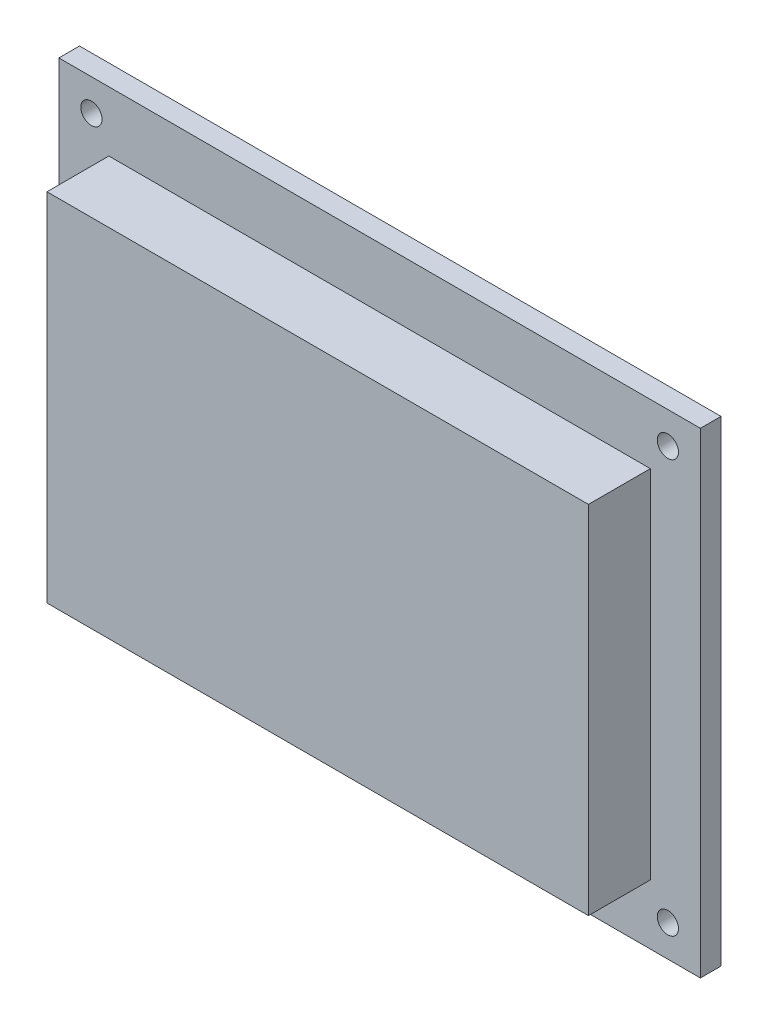
SolidWorks part; units mm, degrees
ref_plane "Front Plane" through (0, 0, 0) normal (0, 0, 1) x (1, 0, 0)
ref_plane "Top Plane" through (0, 0, 0) normal (0, 1, 0) x (1, 0, 0)
ref_plane "Right Plane" through (0, 0, 0) normal (1, 0, 0) x (0, 0, -1)
sketch "Sketch1" plane through (0, 0, 0) normal (0, 0, 1) x (1, 0, 0)
  line L1 (-49.3395, -36.6141) -> (49.3395, -36.6141)
  line L2 (-49.3395, -36.6141) -> (-49.3395, 36.6141)
  line L3 (-49.3395, 36.6141) -> (49.3395, 36.6141)
  line L4 (49.3395, -36.6141) -> (49.3395, 36.6141)
  line L5 (-49.3395, -36.6141) -> (49.3395, 36.6141) construction
  line L6 (-49.3395, 36.6141) -> (49.3395, -36.6141) construction
  point P0 (0, 0)
  dimension "D1" = 73.2282
  dimension "D2" = 98.679
extrude "Boss-Extrude1" add sketch "Sketch1" along normal blind 3.175
sketch "Sketch2" plane through (0, 0, 3.175) normal (0, 0, 1) x (1, 0, 0)
  line L0 (49.3395, 36.6141) -> (-49.3395, 36.6141) construction
  line L1 (-41.6433, -27.3939) -> (41.6433, -27.3939)
  line L2 (-41.6433, -27.3939) -> (-41.6433, 27.3939)
  line L3 (-41.6433, 27.3939) -> (41.6433, 27.3939)
  line L4 (41.6433, -27.3939) -> (41.6433, 27.3939)
  line L5 (-41.6433, -27.3939) -> (41.6433, 27.3939) construction
  line L6 (-41.6433, 27.3939) -> (41.6433, -27.3939) construction
  line L7 (-49.3395, 36.6141) -> (-49.3395, -36.6141) construction
  point P0 (0, 0)
  dimension "D1" = 9.2202
  dimension "D2" = 7.6962
extrude "Boss-Extrude2" add sketch "Sketch2" along normal blind 9.525
sketch "Sketch3" plane through (0, 0, 12.7) normal (0, 0, 1) x (1, 0, 0)
  line L0 (49.3395, 36.6141) -> (-49.3395, 36.6141) construction
  line L1 (-44.3357, -31.7373) -> (44.3357, -31.7373) construction
  line L2 (-44.3357, -31.7373) -> (-44.3357, 31.7373) construction
  line L3 (-44.3357, 31.7373) -> (44.3357, 31.7373) construction
  line L4 (44.3357, -31.7373) -> (44.3357, 31.7373) construction
  line L5 (-44.3357, -31.7373) -> (44.3357, 31.7373) construction
  line L6 (-44.3357, 31.7373) -> (44.3357, -31.7373) construction
  line L7 (-49.3395, 36.6141) -> (-49.3395, -36.6141) construction
  point P0 (0, 0)
  dimension "D1" = 4.8768
  dimension "D2" = 5.0038
hole_wizard "#4 Clearance Hole1" positions "3DSketch1" profile "Sketch4" hole size "#4" standard "ANSI Inch" end condition up to next
sketch3d "3DSketch1"
  point P0 (-44.3357, 31.7373, 12.7)
  point P3 (44.3357, 31.7373, 12.7)
  point P6 (44.3357, -31.7373, 12.7)
  point P9 (-44.3357, -31.7373, 12.7)
sketch "Sketch4" plane through (-44.3357, 31.7373, 12.7) normal (1, 0, 0) x (0, -1, 0)
  line L0 (0, 0) -> (0, 12.7)
  line L1 (0, 12.7) -> (1.6319, 12.7)
  line L2 (1.6319, 12.7) -> (1.6319, 0)
  line L5 (1.6319, 0) -> (0, 0)
  line L11 (0, -6.35) -> (0, 107.95) construction
  dimension "Thru Hole Dia." = 3.2639
  dimension "Thru Hole Depth" = 12.7
